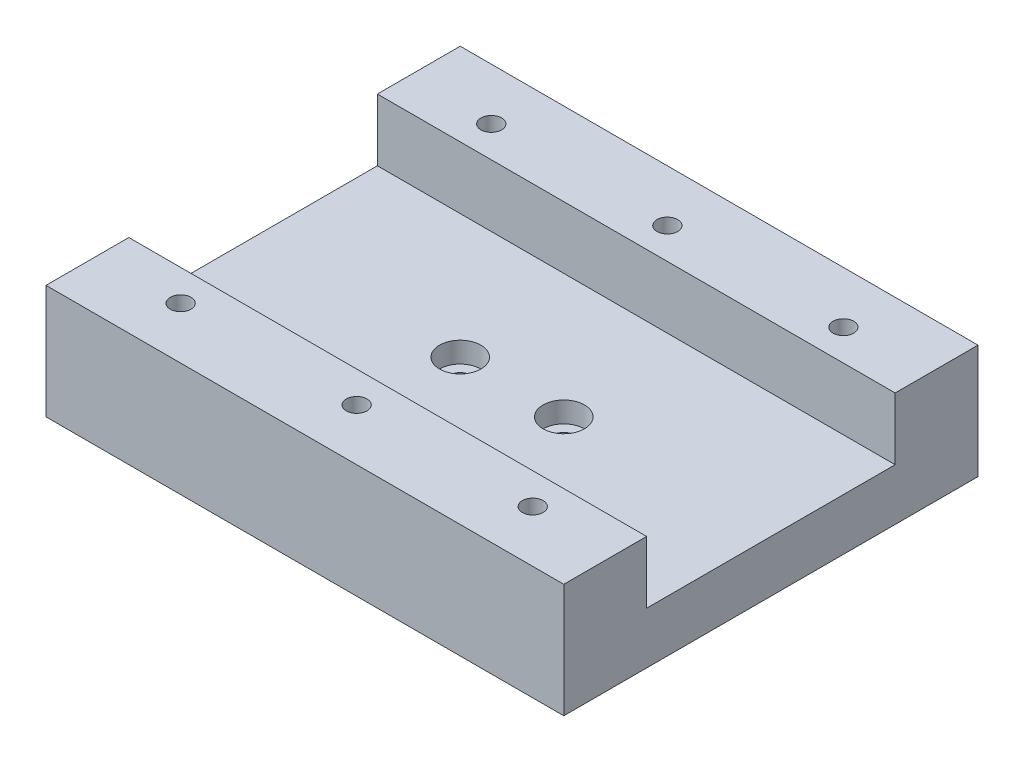
SolidWorks part; units mm, degrees
material "1060 Alloy"
ref_plane "Front Plane" through (0, 0, 0) normal (0, 0, 1) x (1, 0, 0)
ref_plane "Top Plane" through (0, 0, 0) normal (0, 1, 0) x (1, 0, 0)
ref_plane "Right Plane" through (0, 0, 0) normal (1, 0, 0) x (0, 0, -1)
sketch "Sketch1" plane through (0, 0, 0) normal (0, 1, 0) x (1, 0, 0)
  line L1 (-25, 20) -> (25, 20)
  line L2 (-25, 20) -> (-25, -20)
  line L3 (-25, -20) -> (25, -20)
  line L4 (25, 20) -> (25, -20)
  line L5 (-25, 20) -> (25, -20) construction
  line L6 (-25, -20) -> (25, 20) construction
  point P0 (0, 0)
  dimension "D1" = 40
  dimension "D2" = 50
extrude "Boss-Extrude1" add sketch "Sketch1" along normal blind 5
sketch "Sketch2" plane through (0, 5, 0) normal (0, 1, 0) x (1, 0, 0)
  line L0 (-5, 0) -> (5, 0) construction
  circle A0 centre (-5, 0) radius 1
  circle A1 centre (5, 0) radius 1
  point P4 (0, 0)
  dimension "D2" = 2
  dimension "D3" = 2
  dimension "D1" = 10
extrude "Cut-Extrude1" cut sketch "Sketch2" against normal through all
sketch "Sketch3" plane through (0, 5, 0) normal (0, 1, 0) x (1, 0, 0)
  circle A0 centre (-5, 0) radius 2
  circle A1 centre (5, 0) radius 2
  dimension "D1" = 4
  dimension "D2" = 4
extrude "Cut-Extrude2" cut sketch "Sketch3" against normal blind 2
sketch "Sketch5" plane through (0, 5, 0) normal (0, 1, 0) x (1, 0, 0)
  line L0 (25, -20) -> (25, 20) construction
  line L1 (-25, 20) -> (25, 20)
  line L2 (-25, 20) -> (-25, 12)
  line L3 (-25, 12) -> (25, 12)
  line L4 (25, 20) -> (25, 12)
  line L6 (-25, -20) -> (25, -20)
  line L7 (-25, -20) -> (-25, -12)
  line L8 (-25, -12) -> (25, -12)
  line L9 (25, -20) -> (25, -12)
  dimension "D1" = 8
  dimension "D2" = 8
extrude "Boss-Extrude2" add sketch "Sketch5" along normal blind 6
sketch "Sketch4" plane through (0, 5, 0) normal (0, 1, 0) x (1, 0, 0)
  line L0 (0, 20) -> (0, -20) construction
  line L1 (25, 20) -> (-25, 20) construction
  line L2 (-25, -20) -> (25, -20) construction
  circle A0 centre (-17, 15) radius 1
  circle A1 centre (0, 15) radius 1
  circle A2 centre (17, 15) radius 1
  circle A3 centre (-17, -15) radius 1
  circle A4 centre (0, -15) radius 1
  circle A5 centre (17, -15) radius 1
  dimension "D1" = 2
  dimension "D2" = 2
  dimension "D3" = 2
  dimension "D4" = 2
  dimension "D5" = 2
  dimension "D6" = 2
  dimension "D7" = 15
  dimension "D8" = 15
  dimension "D9" = 17
  dimension "D10" = 17
  dimension "D11" = 17
  dimension "D12" = 17
extrude "Cut-Extrude3" cut sketch "Sketch4" against normal through all both and the other way through all
